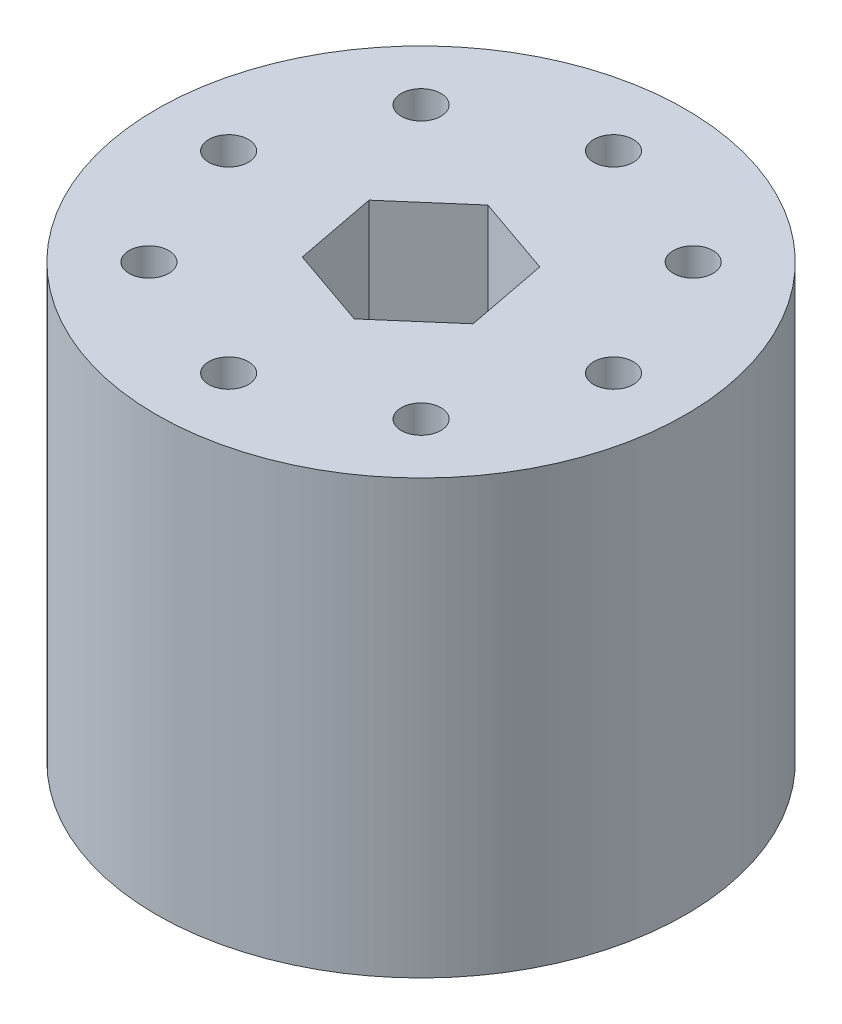
SolidWorks part; units mm, degrees
ref_plane "Front Plane" through (0, 0, 0) normal (0, 0, 1) x (1, 0, 0)
ref_plane "Top Plane" through (0, 0, 0) normal (0, 1, 0) x (1, 0, 0)
ref_plane "Right Plane" through (0, 0, 0) normal (1, 0, 0) x (0, 0, -1)
sketch "Sketch1" plane through (0, 0, 0) normal (0, 1, 0) x (1, 0, 0)
  circle A0 centre (0, 0) radius 22
extrude "Boss-Extrude1" add sketch "Sketch1" along normal blind 36
sketch "Sketch2" plane through (0, 36, 0) normal (0, 1, 0) x (1, 0, 0)
  line L0 (-11.3137, 11.3137) -> (11.3137, -11.3137) construction
  line L1 (11.3137, 11.3137) -> (-11.3137, -11.3137) construction
  line L2 (0, 16) -> (0, -16) construction
  line L3 (16, 0) -> (-16, 0) construction
  circle A3 centre (-11.3137, 11.3137) radius 1.65
  circle A4 centre (0, 16) radius 1.65
  circle A62 centre (16, 0) radius 1.65
  circle A63 centre (11.3137, 11.3137) radius 1.65
  circle A64 centre (0, -16) radius 1.65
  circle A65 centre (11.3137, -11.3137) radius 1.65
  circle A66 centre (-16, 0) radius 1.65
  circle A67 centre (-11.3137, -11.3137) radius 1.65
  circle A68 centre (-16, 0) radius 1.65 [skipped]
  circle A69 centre (-11.3137, -11.3137) radius 1.65 [skipped]
  circle A70 centre (0, -16) radius 1.65 [skipped]
  circle A71 centre (11.3137, -11.3137) radius 1.65 [skipped]
  circle A72 centre (16, 0) radius 1.65 [skipped]
  circle A73 centre (11.3137, 11.3137) radius 1.65 [skipped]
  point P25 (0, 0)
  point P43 (0, 0)
  point P172 (-1.004, 0.3293)
  dimension "D3" = 32
  dimension "D5" = 8
  dimension "D16" = 4
  dimension "D4" = 32
  dimension "D6" = 32
extrude "Cut-Extrude1" cut sketch "Sketch2" against normal through all both and the other way through all
sketch "Sketch3" plane through (0, 36, 0) normal (0, 1, 0) x (1, 0, 0)
  line L1 (1.3217, -6.8741) -> (6.614, -2.2924)
  line L2 (6.614, -2.2924) -> (5.2923, 4.5817)
  line L3 (5.2923, 4.5817) -> (-1.3217, 6.8741)
  line L4 (-1.3217, 6.8741) -> (-6.614, 2.2924)
  line L5 (-6.614, 2.2924) -> (-5.2923, -4.5817)
  line L6 (-5.2923, -4.5817) -> (1.3217, -6.8741)
  circle A0 centre (0, 0) radius 6.0622 construction
  dimension "D1" = 7
extrude "Cut-Extrude2" cut sketch "Sketch3" against normal blind 10
sketch "Sketch4" plane through (0, 26, 0) normal (0, 1, 0) x (1, 0, 0)
  circle A0 centre (0, 0) radius 2.3
extrude "Cut-Extrude3" cut sketch "Sketch4" against normal blind 38
sketch "Sketch5" plane through (0, 0, 0) normal (0, -1, 0) x (-1, 0, 0)
  circle A0 centre (0, 0) radius 5.5954
extrude "Cut-Extrude4" cut sketch "Sketch5" against normal blind 9
